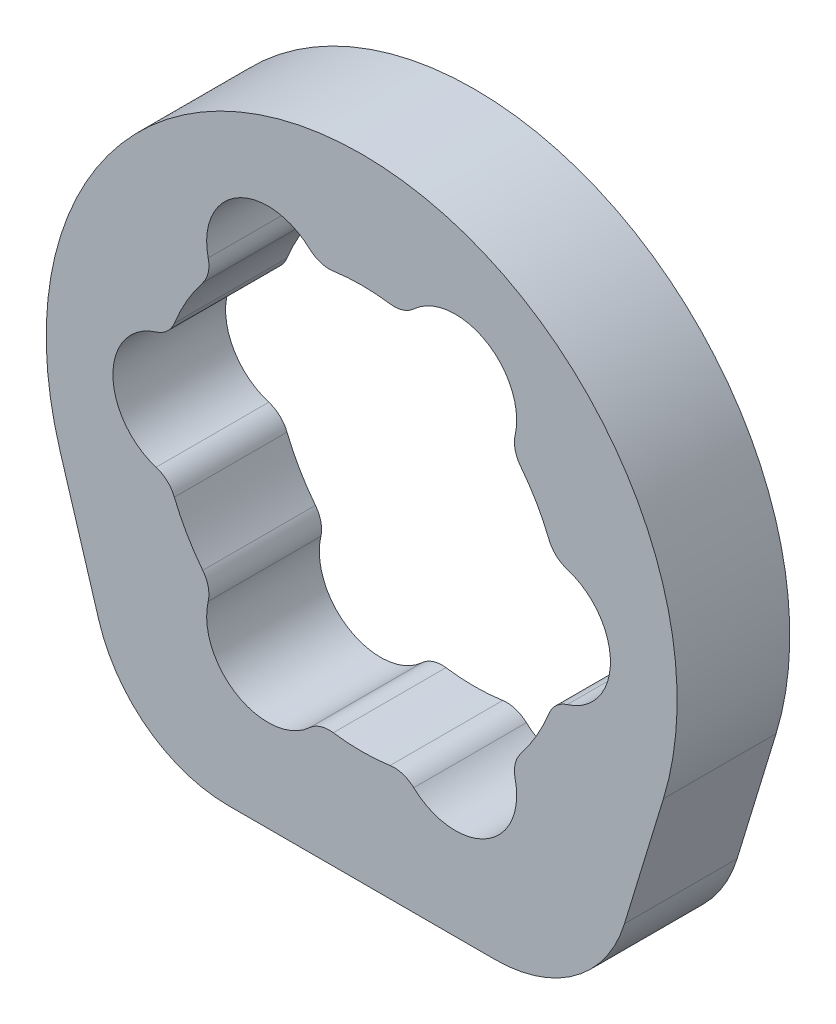
SolidWorks part; units mm, degrees
ref_plane "Front Plane" through (0, 0, 0) normal (0, 0, 1) x (1, 0, 0)
ref_plane "Top Plane" through (0, 0, 0) normal (0, 1, 0) x (1, 0, 0)
ref_plane "Right Plane" through (0, 0, 0) normal (1, 0, 0) x (0, 0, -1)
sketch "Sketch1" plane through (0, 0, 0) normal (0, 0, 1) x (1, 0, 0)
  line L0 (-16.4583, -22.225) -> (16.4583, -22.225)
  line L1 (-21.2587, -6.4823) -> (-10.6293, -41.3411)
  line L2 (21.2587, -6.4823) -> (10.6293, -41.3411)
  circle A1 centre (0, 0) radius 14.224
  circle A2 centre (-6.604, 11.4385) radius 4.318
  circle A3 centre (6.604, 11.4385) radius 4.318
  circle A4 centre (13.208, 0) radius 4.318
  circle A5 centre (6.604, -11.4385) radius 4.318
  circle A6 centre (-6.604, -11.4385) radius 4.318
  circle A7 centre (-13.208, 0) radius 4.318
  circle A8 centre (0, 0) radius 22.225
  circle A9 centre (0, -38.1) radius 6.477
  circle A10 centre (0, -38.1) radius 11.1125
  point P18 (0, 0)
  dimension "D1" = 44.45
  dimension "D2" = 28.448
  dimension "D4" = 8.636
  dimension "D8" = 12.954
  dimension "D9" = 22.225
  dimension "D3" = 13.208
  dimension "D6" = 38.1
  dimension "D5" = 6
extrude "Boss-Extrude1" add sketch "Sketch1" along normal mid plane 7.9375
fillet "Fillet2" radius 2.032 12 edges at (-13.5573, 4.3039, 0) (-13.5572, -4.3039, 0) (-10.5059, -9.589, 0) (-3.0514, -13.8928, 0) (3.0514, -13.8928, 0) (10.5059, -9.589, 0) (13.5572, -4.3039, 0) (13.5572, 4.3039, 0) (10.5059, 9.589, 0) (3.0514, 13.8928, 0) (-3.0514, 13.8928, 0) (-10.5059, 9.589, 0)
fillet "Fillet3" radius 9.525 2 edges at (-16.4583, -22.225, 0) (16.4583, -22.225, 0)
